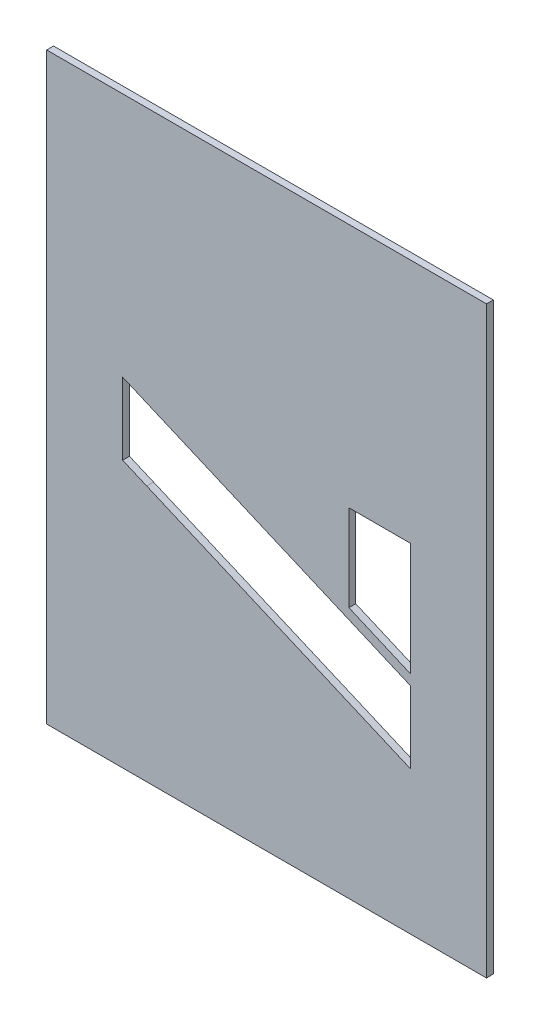
SolidWorks part; units mm, degrees
ref_plane "前基準面" through (0, 0, 0) normal (0, 0, 1) x (1, 0, 0)
ref_plane "上基準面" through (0, 0, 0) normal (0, 1, 0) x (1, 0, 0)
ref_plane "右基準面" through (0, 0, 0) normal (1, 0, 0) x (0, 0, -1)
sketch "草圖1" plane through (0, 0, 0) normal (0, 0, 1) x (1, 0, 0)
  line L1 (152.75, -610.575) -> (-152.75, -610.575)
  line L2 (152.75, -610.575) -> (152.75, 610.575)
  line L3 (152.75, 610.575) -> (-152.75, 610.575)
  line L4 (-152.75, -610.575) -> (-152.75, 610.575)
  line L5 (152.75, -610.575) -> (-152.75, 610.575) construction
  line L6 (152.75, 610.575) -> (-152.75, -610.575) construction
  point P0 (0, 0)
  dimension "D1" = 1221.15
  dimension "D2" = 305.5
extrude "填料-伸長1" add sketch "草圖1" along normal blind 4.75
sketch "草圖2" plane through (0, 0, 4.75) normal (0, 0, 1) x (1, 0, 0)
  line L0 (-152.75, 610.575) -> (-99.975, 610.575) construction
  line L1 (152.75, 610.575) -> (-152.75, 610.575) construction
  line L2 (-99.975, 610.575) -> (-99.975, -610.575) construction
  line L3 (-152.75, -610.575) -> (152.75, -610.575) construction
  text T0 "7636" font "Coburn" height 200
  dimension "D1" = 52.775
extrude "除料-伸長2" cut sketch "草圖2" against normal blind 4.75
sketch "草圖6" plane through (0, 0, 4.75) normal (0, 0, 1) x (1, 0, 0)
  line L0 (-152.75, 610.575) -> (-152.75, 205.025) construction
  line L1 (-152.75, 610.575) -> (-152.75, -610.575) construction
  line L2 (-152.75, 205.025) -> (152.75, 205.025)
  line L3 (152.75, -610.575) -> (152.75, 610.575) construction
  dimension "D1" = 405.55
split "分割1" trim tools "草圖6" bodies to split 103 resulting bodies 104
